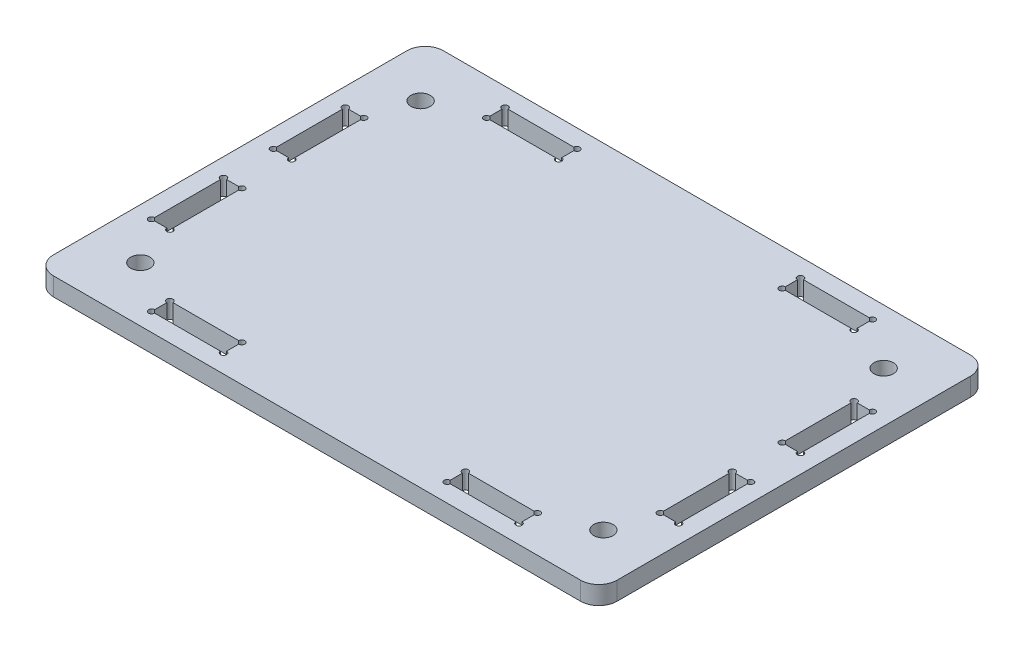
SolidWorks part; units mm, degrees
material "Acrylic (Medium-high impact)"
ref_plane "Front Plane" through (0, 0, 0) normal (0, 0, 1) x (1, 0, 0)
ref_plane "Top Plane" through (0, 0, 0) normal (0, 1, 0) x (1, 0, 0)
ref_plane "Right Plane" through (0, 0, 0) normal (1, 0, 0) x (0, 0, -1)
sketch "Sketch5" plane through (0, 0, 0) normal (0, 1, 0) x (1, 0, 0)
  line L1 (0, 0) -> (80, 0) construction
  line L2 (0, 0) -> (0, 50) construction
  line L3 (0, 50) -> (80, 50) construction
  line L4 (80, 0) -> (80, 50) construction
  line L5 (4.5, -0.75) -> (75.5, -0.75) construction
  line L6 (4.5, -0.75) -> (4.5, 50.75) construction
  line L7 (4.5, 50.75) -> (75.5, 50.75) construction
  line L8 (75.5, -0.75) -> (75.5, 50.75) construction
  line L9 (-3.25, -7) -> (83.25, -7)
  line L10 (-6.25, -4) -> (-6.25, 54)
  line L11 (-3.25, 57) -> (83.25, 57)
  line L12 (86.25, -4) -> (86.25, 54)
  circle A0 centre (2, 2) radius 1.5875
  circle A1 centre (2, 48) radius 1.5875
  circle A2 centre (78, 48) radius 1.5875
  circle A3 centre (78, 2) radius 1.5875
  arc A4 (-6.25, -4) -> (-3.25, -7) centre (-3.25, -4) ccw
  arc A5 (-3.25, 57) -> (-6.25, 54) centre (-3.25, 54) ccw
  arc A6 (86.25, 54) -> (83.25, 57) centre (83.25, 54) ccw
  arc A7 (83.25, -7) -> (86.25, -4) centre (83.25, -4) ccw
  line B0 (10.3533, 54) -> (21.1533, 54)
  line B1 (9.8533, 53.5) -> (9.8533, 51.5)
  line B2 (10.3533, 51) -> (21.1533, 51)
  line B3 (21.6533, 53.5) -> (21.6533, 51.5)
  arc B4 (10.3533, 54) -> (9.8533, 53.5) centre (9.8533, 54) ccw
  arc B5 (9.8533, 51.5) -> (10.3533, 51) centre (9.8533, 51) ccw
  arc B6 (21.6533, 53.5) -> (21.1533, 54) centre (21.6533, 54) ccw
  arc B7 (21.1533, 51) -> (21.6533, 51.5) centre (21.6533, 51) ccw
  line B8 (58.85, 54) -> (69.65, 54)
  line B9 (58.35, 53.5) -> (58.35, 51.5)
  line B10 (58.85, 51) -> (69.65, 51)
  line B11 (70.15, 53.5) -> (70.15, 51.5)
  arc B12 (58.85, 54) -> (58.35, 53.5) centre (58.35, 54) ccw
  arc B13 (58.35, 51.5) -> (58.85, 51) centre (58.35, 51) ccw
  arc B14 (70.15, 53.5) -> (69.65, 54) centre (70.15, 54) ccw
  arc B15 (69.65, 51) -> (70.15, 51.5) centre (70.15, 51) ccw
  line B16 (10.35, -1) -> (21.15, -1)
  line B17 (9.85, -1.5) -> (9.85, -3.5)
  line B18 (10.35, -4) -> (21.15, -4)
  line B19 (21.65, -1.5) -> (21.65, -3.5)
  arc B20 (10.35, -1) -> (9.85, -1.5) centre (9.85, -1) ccw
  arc B21 (9.85, -3.5) -> (10.35, -4) centre (9.85, -4) ccw
  arc B22 (21.65, -1.5) -> (21.15, -1) centre (21.65, -1) ccw
  arc B23 (21.15, -4) -> (21.65, -3.5) centre (21.65, -4) ccw
  line B24 (58.85, -1) -> (69.65, -1)
  line B25 (58.35, -1.5) -> (58.35, -3.5)
  line B26 (58.85, -4) -> (69.65, -4)
  line B27 (70.15, -1.5) -> (70.15, -3.5)
  arc B28 (58.85, -1) -> (58.35, -1.5) centre (58.35, -1) ccw
  arc B29 (58.35, -3.5) -> (58.85, -4) centre (58.35, -4) ccw
  arc B30 (70.15, -1.5) -> (69.65, -1) centre (70.15, -1) ccw
  arc B31 (69.65, -4) -> (70.15, -3.5) centre (70.15, -4) ccw
  line B32 (-3.25, 9.6) -> (-3.25, 20.4)
  line B33 (-2.75, 9.1) -> (-0.75, 9.1)
  line B34 (-0.25, 9.6) -> (-0.25, 20.4)
  line B35 (-2.75, 20.9) -> (-0.75, 20.9)
  arc B36 (-3.25, 9.6) -> (-2.75, 9.1) centre (-3.25, 9.1) ccw
  arc B37 (-0.75, 9.1) -> (-0.25, 9.6) centre (-0.25, 9.1) ccw
  arc B38 (-2.75, 20.9) -> (-3.25, 20.4) centre (-3.25, 20.9) ccw
  arc B39 (-0.25, 20.4) -> (-0.75, 20.9) centre (-0.25, 20.9) ccw
  line B40 (-3.25, 29.6) -> (-3.25, 40.4)
  line B41 (-2.75, 29.1) -> (-0.75, 29.1)
  line B42 (-0.25, 29.6) -> (-0.25, 40.4)
  line B43 (-2.75, 40.9) -> (-0.75, 40.9)
  arc B44 (-3.25, 29.6) -> (-2.75, 29.1) centre (-3.25, 29.1) ccw
  arc B45 (-0.75, 29.1) -> (-0.25, 29.6) centre (-0.25, 29.1) ccw
  arc B46 (-2.75, 40.9) -> (-3.25, 40.4) centre (-3.25, 40.9) ccw
  arc B47 (-0.25, 40.4) -> (-0.75, 40.9) centre (-0.25, 40.9) ccw
  line B48 (80.25, 9.6) -> (80.25, 20.4)
  line B49 (80.75, 9.1) -> (82.75, 9.1)
  line B50 (83.25, 9.6) -> (83.25, 20.4)
  line B51 (80.75, 20.9) -> (82.75, 20.9)
  arc B52 (80.25, 9.6) -> (80.75, 9.1) centre (80.25, 9.1) ccw
  arc B53 (82.75, 9.1) -> (83.25, 9.6) centre (83.25, 9.1) ccw
  arc B54 (80.75, 20.9) -> (80.25, 20.4) centre (80.25, 20.9) ccw
  arc B55 (83.25, 20.4) -> (82.75, 20.9) centre (83.25, 20.9) ccw
  line B56 (80.25, 29.6) -> (80.25, 40.4)
  line B57 (80.75, 29.1) -> (82.75, 29.1)
  line B58 (83.25, 29.6) -> (83.25, 40.4)
  line B59 (80.75, 40.9) -> (82.75, 40.9)
  arc B60 (80.25, 29.6) -> (80.75, 29.1) centre (80.25, 29.1) ccw
  arc B61 (82.75, 29.1) -> (83.25, 29.6) centre (83.25, 29.1) ccw
  arc B62 (80.75, 40.9) -> (80.25, 40.4) centre (80.25, 40.9) ccw
  arc B63 (83.25, 40.4) -> (82.75, 40.9) centre (83.25, 40.9) ccw
  dimension "D3" = 71
  dimension "D4" = 51.5
  dimension "D1" = 80
  dimension "D2" = 50
  dimension "D43" = 16.1
  dimension "D15" = 3.175
  dimension "D12" = 3.175
  dimension "D18" = 3.175
  dimension "D21" = 6.25
  dimension "D27" = 3
  dimension "D29" = 64
  dimension "D38" = 3
  dimension "D40" = 3
  dimension "D39" = 16.1
  dimension "D46" = 3
  dimension "D7" = 3.175
  dimension "D13" = 2
  dimension "D23" = 3
  dimension "D20" = 3
  dimension "D19" = 3
  dimension "D33" = 16.1
  dimension "D37" = 16.1
  dimension "D34" = 3
  dimension "D35" = 16.1
  dimension "D36" = 3
  dimension "D5" = 0.75
  dimension "D6" = 4.5
  dimension "D8" = 2
  dimension "D9" = 2
  dimension "D10" = 2
  dimension "D11" = 2
  dimension "D14" = 2
  dimension "D16" = 2
  dimension "D17" = 2
  dimension "D22" = 6.25
  dimension "D24" = 3
  dimension "D25" = 3
  dimension "D26" = 3
  dimension "D28" = 3
  dimension "D30" = 92.5
  dimension "D31" = 16.1033
  dimension "D32" = 3
  dimension "D41" = 3
  dimension "D42" = 16.1
  dimension "D44" = 3
  dimension "D45" = 16.1
sketch_block_instance "Block2-1"
sketch_block "Block2" parameters "D3"=0.5, "D4"=0.5, "D5"=0.5, "D6"=0.5, "D1"=10.8, "D2"=2, "D7"=10.8, "D8"=2, "D9"=11.8, "D10"=3, "D11"=3, "D12"=11.8
sketch_block_instance "Block2-2"
sketch_block_instance "Block2-3"
sketch_block_instance "Block2-4"
sketch_block_instance "Block2-5"
sketch_block_instance "Block2-6"
sketch_block_instance "Block2-7"
sketch_block_instance "Block2-8"
extrude "Boss-Extrude1" add sketch "Sketch5" along normal blind 3
